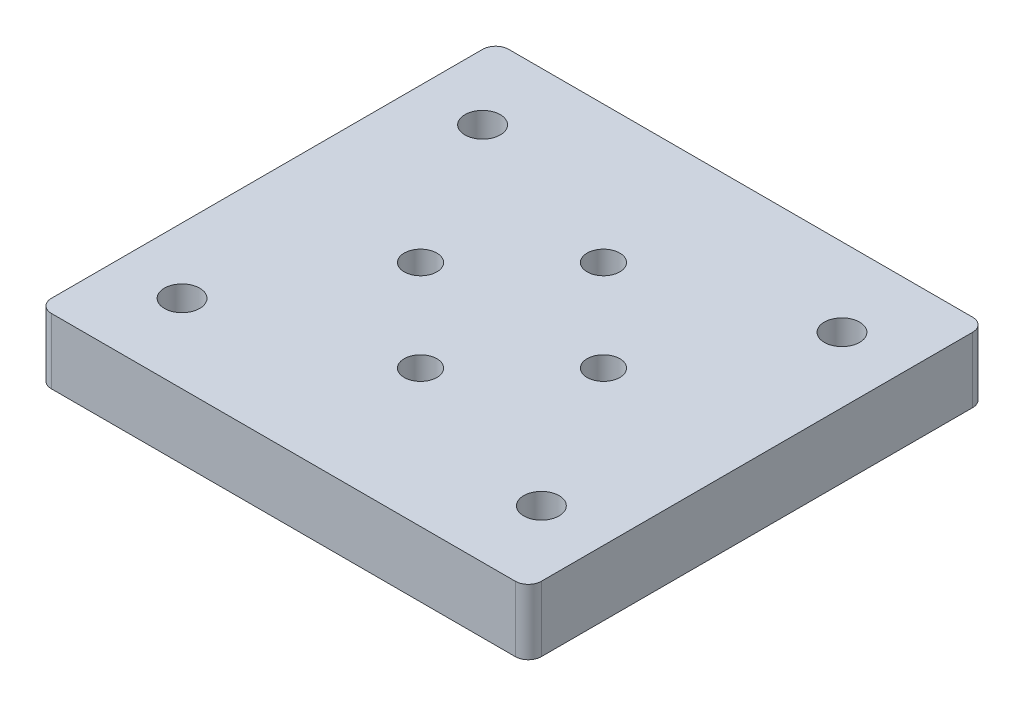
SolidWorks part; units mm, degrees
ref_plane "Front Plane" through (0, 0, 0) normal (0, 0, 1) x (1, 0, 0)
ref_plane "Top Plane" through (0, 0, 0) normal (0, 1, 0) x (1, 0, 0)
ref_plane "Right Plane" through (0, 0, 0) normal (1, 0, 0) x (0, 0, -1)
sketch "Sketch1" plane through (0, 0, 0) normal (0, 1, 0) x (1, 0, 0)
  circle A0 centre (0, 0) radius 11
  circle A1 centre (0, 0) radius 7 construction
  circle A2 centre (0, 7) radius 1.25
  circle A3 centre (7, 0) radius 1.25
  circle A4 centre (0, -7) radius 1.25
  circle A5 centre (-7, 0) radius 1.25
  dimension "D1" = 14
  dimension "D2" = 2.5
  dimension "D3" = 22
extrude "Boss-Extrude1" add sketch "Sketch1" along normal blind 5
sketch "Sketch2" plane through (0, 5, 0) normal (0, 1, 0) x (1, 0, 0)
  line L0 (16.75, 17.5) -> (16.75, -17.5) construction
  line L1 (-17.75, -17.5) -> (17.75, -17.5)
  line L2 (-18.75, -16.5) -> (-18.75, 16.5)
  line L3 (-17.75, 17.5) -> (17.75, 17.5)
  line L4 (18.75, -16.5) -> (18.75, 16.5)
  line L5 (-18.75, -17.5) -> (18.75, 17.5) construction
  line L6 (-18.75, 17.5) -> (18.75, -17.5) construction
  line L7 (4, 17.5) -> (4, -17.5) construction
  circle A0 centre (0, -7) radius 1.25 construction
  circle A1 centre (7, 0) radius 1.25 construction
  circle A2 centre (0, 7) radius 1.25 construction
  circle A3 centre (-7, 0) radius 1.25 construction
  circle A4 centre (0, 0) radius 11 construction
  circle A5 centre (0, -7) radius 1.25
  circle A6 centre (7, 0) radius 1.25
  circle A7 centre (0, 7) radius 1.25
  circle A8 centre (-7, 0) radius 1.25
  circle A9 centre (0, 0) radius 11
  circle A10 centre (-13.75, 11.5) radius 1.35
  circle A11 centre (-13.75, -11.5) radius 1.35
  circle A12 centre (13.75, -11.5) radius 1.35
  circle A13 centre (13.75, 11.5) radius 1.35
  arc A14 (-17.75, -17.5) -> (-18.75, -16.5) centre (-17.75, -16.5) cw
  arc A15 (17.75, -17.5) -> (18.75, -16.5) centre (17.75, -16.5) ccw
  arc A16 (17.75, 17.5) -> (18.75, 16.5) centre (17.75, 16.5) cw
  arc A17 (-18.75, 16.5) -> (-17.75, 17.5) centre (-17.75, 16.5) cw
  point P0 (0, 0)
  circle M6 centre (0, -7) radius 1.25
  circle M7 centre (0, 7) radius 1.25
  circle M8 centre (0, 0) radius 11
  circle M9 centre (7, 0) radius 1.25
  circle M10 centre (-7, 0) radius 1.25
  dimension "D3" = 2.7
  dimension "D8" = 1
  dimension "D1" = 37.5
  dimension "D2" = 35
  dimension "D4" = 5
  dimension "D5" = 5
  dimension "D6" = 6
  dimension "D7" = 6
  dimension "D9" = 3
  dimension "D10" = 4
extrude "Boss-Extrude2" add sketch "Sketch2" along normal blind 5 contours L1 L4 L3 L2 M8 | M8 M7 M9 M10 M6
fillet "Fillet1" radius 0.5 1 edges at (0, 5, 11)
